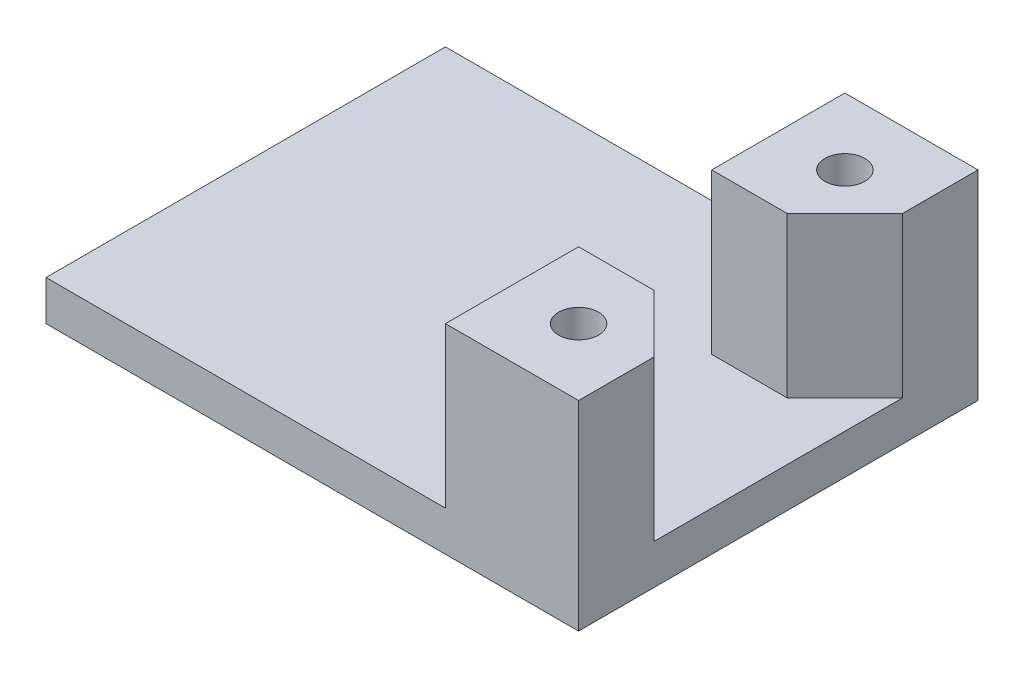
SolidWorks part; units mm, degrees
ref_plane "Front Plane" through (0, 0, 0) normal (0, 0, 1) x (1, 0, 0)
ref_plane "Top Plane" through (0, 0, 0) normal (0, 1, 0) x (1, 0, 0)
ref_plane "Right Plane" through (0, 0, 0) normal (1, 0, 0) x (0, 0, -1)
sketch "Sketch1" plane through (0, 0, 0) normal (0, 1, 0) x (1, 0, 0)
  line L1 (-59.5562, 31.8226) -> (-19.5562, 31.8226)
  line L2 (-59.5562, 31.8226) -> (-59.5562, 1.8226)
  line L3 (-59.5562, 1.8226) -> (-19.5562, 1.8226)
  line L4 (-19.5562, 31.8226) -> (-19.5562, 1.8226)
  circle A0 centre (-24.5562, 26.8226) radius 1.5
  circle A1 centre (-24.5562, 6.8226) radius 1.5
  dimension "D7" = 3
  dimension "D8" = 3
  dimension "D1" = 40
  dimension "D2" = 30
  dimension "D3" = 20
  dimension "D4" = 5
  dimension "D5" = 5
  dimension "D6" = 5
extrude "Boss-Extrude1" add sketch "Sketch1" along normal blind 15
sketch "Sketch2" plane through (0, 15, 0) normal (0, 1, 0) x (1, 0, 0)
  line L0 (-19.5562, 31.8226) -> (-59.5562, 31.8226) construction
  line L1 (-59.5562, 31.8226) -> (-29.5562, 31.8226)
  line L2 (-59.5562, 31.8226) -> (-59.5562, 1.8226)
  line L3 (-59.5562, 1.8226) -> (-29.5562, 1.8226)
  line L4 (-29.5562, 31.8226) -> (-29.5562, 1.8226)
  line L5 (-59.5562, 1.8226) -> (-19.5562, 1.8226) construction
  line L6 (-59.5562, 31.8226) -> (-59.5562, 1.8226) construction
  circle A0 centre (-24.5562, 26.8226) radius 1.5 construction
  dimension "D4" = 5
  dimension "D1" = 0
  dimension "D2" = 0
  dimension "D3" = 0
extrude "Cut-Extrude1" cut sketch "Sketch2" against normal blind 12
sketch "Sketch3" plane through (0, 15, 0) normal (0, 1, 0) x (1, 0, 0)
  line L0 (-29.5562, 1.8226) -> (-29.5562, 31.8226) construction
  line L1 (-29.5562, 21.8226) -> (-19.5562, 21.8226)
  line L2 (-29.5562, 21.8226) -> (-29.5562, 11.8226)
  line L3 (-29.5562, 11.8226) -> (-19.5562, 11.8226)
  line L4 (-19.5562, 21.8226) -> (-19.5562, 11.8226)
  line L5 (-19.5562, 1.8226) -> (-19.5562, 31.8226) construction
  circle A0 centre (-24.5562, 26.8226) radius 1.5 construction
  circle A1 centre (-24.5562, 6.8226) radius 1.5 construction
  dimension "D1" = 5
  dimension "D2" = 5
extrude "Cut-Extrude2" cut sketch "Sketch3" against normal blind 12
sketch "Sketch4" plane through (0, 15, 0) normal (0, 1, 0) x (1, 0, 0)
  line L0 (-23.8994, 21.8226) -> (-19.5562, 26.1657)
  line L1 (-19.5562, 21.8226) -> (-29.5562, 21.8226) construction
  line L2 (-19.5562, 21.8226) -> (-19.5562, 31.8226) construction
  line L3 (-19.5562, 26.1657) -> (-19.5562, 21.8226)
  line L4 (-19.5562, 21.8226) -> (-23.8994, 21.8226)
  line L5 (-23.8994, 11.8226) -> (-19.5562, 7.4794)
  line L6 (-29.5562, 11.8226) -> (-19.5562, 11.8226) construction
  line L7 (-19.5562, 1.8226) -> (-19.5562, 11.8226) construction
  line L8 (-19.5562, 7.4794) -> (-19.5562, 11.8226)
  line L9 (-19.5562, 11.8226) -> (-23.8994, 11.8226)
  circle A0 centre (-24.5562, 26.8226) radius 1.5 construction
  circle A1 centre (-24.5562, 6.8226) radius 1.5 construction
  dimension "D1" = 4
  dimension "D2" = 4
extrude "Cut-Extrude3" cut sketch "Sketch4" against normal blind 12
